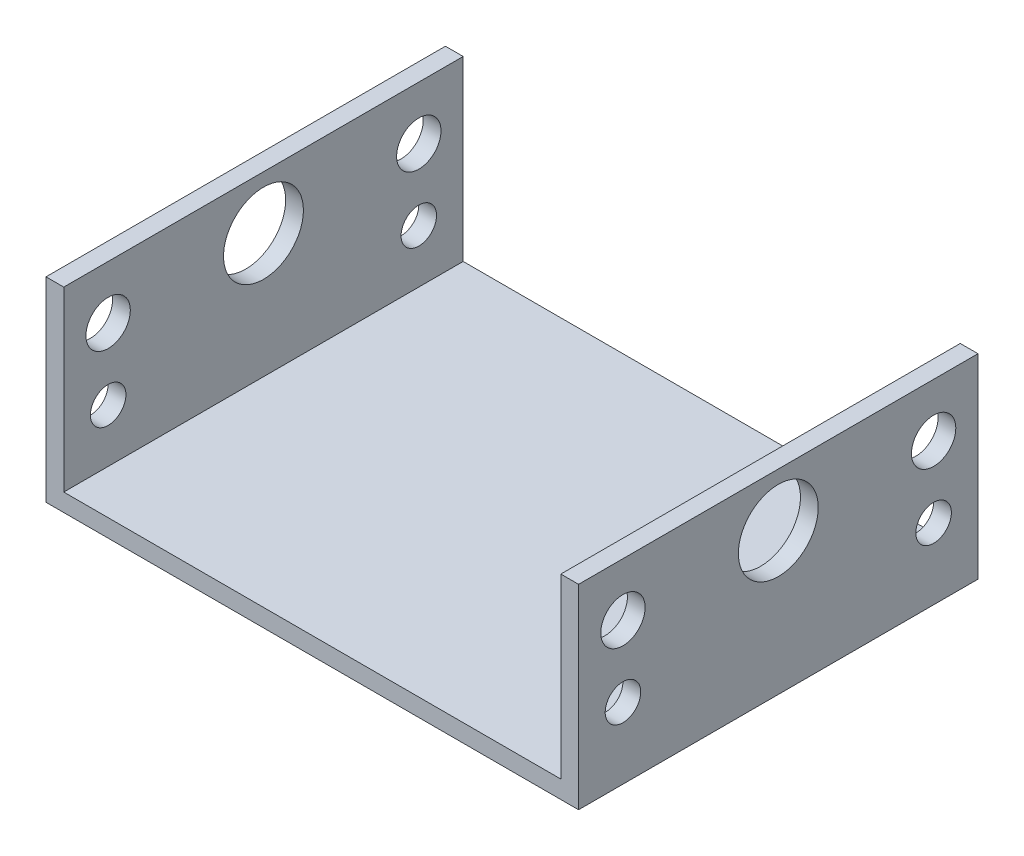
SolidWorks part; units mm, degrees
ref_plane "Front Plane" through (0, 0, 0) normal (0, 0, 1) x (1, 0, 0)
ref_plane "Top Plane" through (0, 0, 0) normal (0, 1, 0) x (1, 0, 0)
ref_plane "Right Plane" through (0, 0, 0) normal (1, 0, 0) x (0, 0, -1)
sketch "Sketch1" plane through (0, 0, 0) normal (0, 1, 0) x (1, 0, 0)
  line L1 (-30, -22.5) -> (30, -22.5)
  line L2 (-30, -22.5) -> (-30, 22.5)
  line L3 (-30, 22.5) -> (30, 22.5)
  line L4 (30, -22.5) -> (30, 22.5)
  line L5 (-30, -22.5) -> (30, 22.5) construction
  line L6 (-30, 22.5) -> (30, -22.5) construction
  point P0 (0, 0)
  dimension "D1" = 60
  dimension "D2" = 45
extrude "Boss-Extrude1" add sketch "Sketch1" along normal blind 2
sketch "Sketch2" plane through (0, 2, 0) normal (0, 1, 0) x (1, 0, 0)
  line L0 (-30, -22.5) -> (30, -22.5) construction
  line L1 (-30, 22.5) -> (-28, 22.5)
  line L2 (-30, 22.5) -> (-30, -22.5)
  line L3 (-30, -22.5) -> (-28, -22.5)
  line L4 (-28, 22.5) -> (-28, -22.5)
  line L6 (30, 22.5) -> (28, 22.5)
  line L7 (30, 22.5) -> (30, -22.5)
  line L8 (30, -22.5) -> (28, -22.5)
  line L9 (28, 22.5) -> (28, -22.5)
  dimension "D1" = 2
  dimension "D2" = 2
extrude "Boss-Extrude2" add sketch "Sketch2" along normal blind 20
sketch "Sketch3" plane through (30, 0, 0) normal (1, 0, 0) x (0, 0, -1)
  circle A0 centre (-17.5, 8) radius 2
  circle A1 centre (17.5, 8) radius 2
  circle A2 centre (0, 16) radius 4.5
  circle A3 centre (17.5, 16) radius 2.5
  circle A4 centre (-17.5, 16) radius 2.5
  point P10 (0, 0)
  point P12 (0, 0)
  point P13 (0, 0)
  point P14 (1.6945, 7.8185)
  point P15 (0, 0)
  point P16 (0, 0)
  point P17 (17.5, 6.1198)
  point P20 (25.2311, 24.4781)
  dimension "D4" = 4
  dimension "D5" = 4
  dimension "D6" = 9
  dimension "D8" = 5
  dimension "D9" = 5
  dimension "D1" = 35
  dimension "D2" = 17.5
  dimension "D3" = 8
  dimension "D7" = 16
extrude "Cut-Extrude1" cut sketch "Sketch3" against normal through all both and the other way through all
